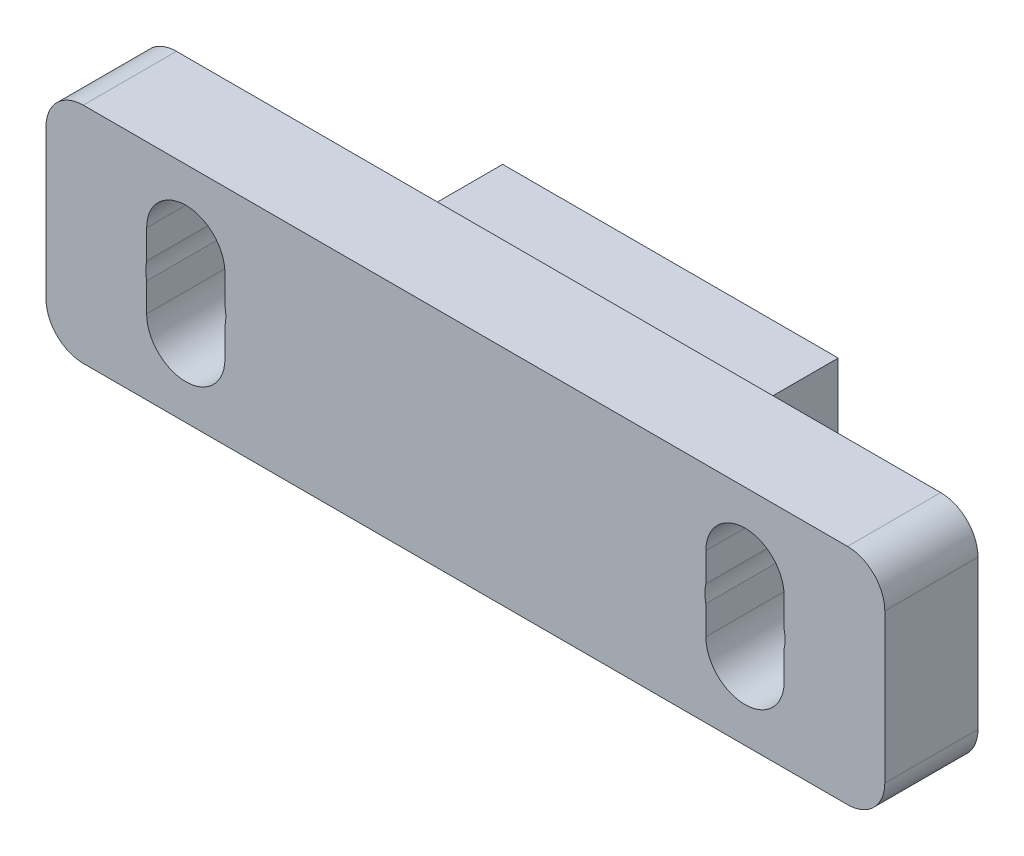
SolidWorks part; units mm, degrees
ref_plane "Front Plane" through (0, 0, 0) normal (0, 0, 1) x (1, 0, 0)
ref_plane "Top Plane" through (0, 0, 0) normal (0, 1, 0) x (1, 0, 0)
ref_plane "Right Plane" through (0, 0, 0) normal (1, 0, 0) x (0, 0, -1)
sketch "Sketch1" plane through (0, 0, 0) normal (0, 0, 1) x (1, 0, 0)
  line L0 (-22.5, 6) -> (22.5, -6) construction
  line L1 (-22.5, 6) -> (22.5, 6)
  line L2 (-22.5, 6) -> (-22.5, -6)
  line L3 (-22.5, -6) -> (22.5, -6)
  line L4 (22.5, 6) -> (22.5, -6)
  line L5 (15, 0) -> (-15, 0) construction
  circle A0 centre (-15, 0) radius 2.15
  circle A1 centre (15, 0) radius 2.15
  dimension "D4" = 4.3
  dimension "D1" = 45
  dimension "D2" = 12
  dimension "D3" = 30
extrude "Boss-Extrude1" add sketch "Sketch1" along normal blind 5
sketch "Sketch2" plane through (0, 0, 5) normal (0, 0, 1) x (1, 0, 0)
  line L0 (-15, 2) -> (-15, -2) construction
  line L1 (-12.9, 2) -> (-12.9, -2)
  line L2 (-17.1, 2) -> (-17.1, -2)
  line L3 (15, -2) -> (15, 2) construction
  line L4 (12.9, -2) -> (12.9, 2)
  line L5 (17.1, -2) -> (17.1, 2)
  arc A0 (-12.9, 2) -> (-17.1, 2) centre (-15, 2) ccw
  arc A1 (-17.1, -2) -> (-12.9, -2) centre (-15, -2) ccw
  arc A2 (12.9, -2) -> (17.1, -2) centre (15, -2) ccw
  arc A3 (17.1, 2) -> (12.9, 2) centre (15, 2) ccw
  circle A4 centre (-15, 0) radius 2.15 construction
  circle A5 centre (15, 0) radius 2.15 construction
  point P2 (-15, 0)
  point P9 (15, 0)
  dimension "D1" = 2.1
  dimension "D2" = 4
extrude "Cut-Extrude1" cut sketch "Sketch2" against normal through all
sketch "Sketch3" plane through (0, 0, 0) normal (0, 0, 1) x (1, 0, 0)
  line L0 (-22.5, -6) -> (22.5, -6) construction
  line L1 (-9, -6) -> (9, -6)
  line L2 (-9, -6) -> (-9, 3.5)
  line L3 (-9, 3.5) -> (9, 3.5)
  line L4 (9, -6) -> (9, 3.5)
  line L5 (0, 6) -> (0, -6) construction
  line L6 (22.5, 6) -> (-22.5, 6) construction
  dimension "D1" = 2.5
  dimension "D2" = 18
extrude "Boss-Extrude2" add sketch "Sketch3" against normal blind 6
fillet "Fillet1" radius 2 4 edges at (-22.5, 6, 2.5) (-22.5, -6, 2.5) (22.5, -6, 2.5) (22.5, 6, 2.5)
